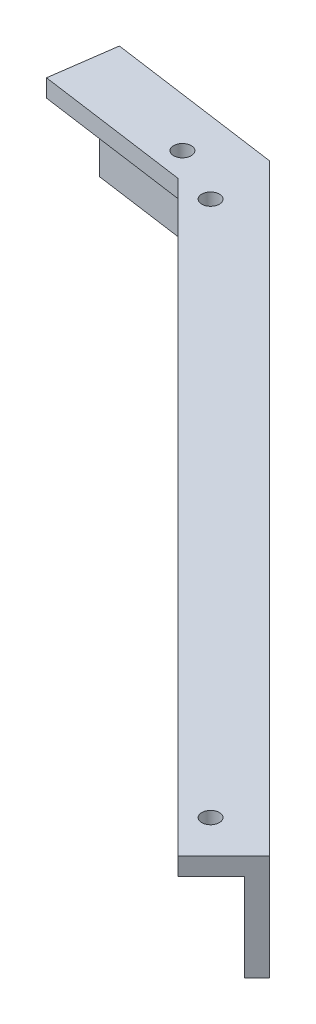
SolidWorks part; units mm, degrees
ref_plane "Alzado" through (0, 0, 0) normal (0, 0, 1) x (1, 0, 0)
ref_plane "Planta" through (0, 0, 0) normal (0, 1, 0) x (1, 0, 0)
ref_plane "Vista lateral" through (0, 0, 0) normal (1, 0, 0) x (0, 0, -1)
sketch "Croquis1" plane through (0, 0, 0) normal (0, 1, 0) x (1, 0, 0)
  line L0 (-35, 0) -> (35, 0) construction
  line L1 (35, 0) -> (65, 0)
  line L2 (65, 0) -> (167.5305, -102.5305)
  line L3 (-35, 0) -> (-65, 0)
  line L4 (-65, 0) -> (-167.5305, -102.5305)
  line L5 (-167.5305, -102.5305) -> (-195, -130) construction
  line L6 (167.5305, -102.5305) -> (195, -130) construction
  line L7 (-167.5305, -102.5305) -> (-161.8736, -108.1873)
  line L8 (167.5305, -102.5305) -> (161.8736, -108.1873)
  line L9 (-161.8736, -108.1873) -> (-61.6863, -8)
  line L10 (-61.6863, -8) -> (-35, -8)
  line L11 (161.8736, -108.1873) -> (61.6863, -8)
  line L12 (61.6863, -8) -> (35, -8)
  line L13 (-35, 0) -> (-35, -8)
  line L14 (35, 0) -> (35, -8)
  line L15 (-65, 0) -> (-62.1716, -2.8284) construction
  line L16 (-62.1716, -2.8284) -> (-67.8284, -8.4853) construction
  line L17 (-67.8284, -8.4853) -> (-159.0452, -99.7021) construction
  line L18 (-159.0452, -99.7021) -> (-164.7021, -105.3589) construction
  line L19 (65, 0) -> (62.1716, -2.8284) construction
  line L20 (62.1716, -2.8284) -> (67.8284, -8.4853) construction
  circle A0 centre (-50, -4) radius 1.5
  circle A1 centre (50, -4) radius 1.5
  circle A2 centre (-67.8284, -8.4853) radius 1.5
  circle A3 centre (-159.0452, -99.7021) radius 1.5
  circle A4 centre (159.0452, -99.7021) radius 1.5
  circle A5 centre (67.8284, -8.4853) radius 1.5
  dimension "D19" = 15
  dimension "D21" = 3
  dimension "D22" = 15
  dimension "D23" = 90
  dimension "D29" = 4
  dimension "D31" = 8
  dimension "D1" = 0
  dimension "D2" = 145
  dimension "D3" = 390
  dimension "D4" = 30
  dimension "D5" = 30
  dimension "D6" = 35
  dimension "D7" = 35
  dimension "D8" = 145
  dimension "D9" = 0
  dimension "D10" = 90
  dimension "D11" = 90
  dimension "D12" = 90
  dimension "D13" = 0
  dimension "D14" = 8
  dimension "D15" = 8
  dimension "D16" = 8
  dimension "D17" = 0
  dimension "D18" = 8
  dimension "D20" = 4
  dimension "D24" = 90
  dimension "D25" = 180
  dimension "D26" = 4
  dimension "D27" = 8
  dimension "D28" = 8
  dimension "D30" = 4
  dimension "D32" = 90
  dimension "D33" = 4
  dimension "D34" = 8
extrude "Saliente-Extruir2" add sketch "Croquis1" along normal blind 3
sketch "Croquis3" plane through (0, 3, 0) normal (0, 1, 0) x (1, 0, 0)
  line L0 (-161.8736, -108.1873) -> (-159.7523, -110.3087)
  line L1 (-159.7523, -110.3087) -> (-60.4437, -11)
  line L2 (-60.4437, -11) -> (-35, -11)
  line L3 (-35, -11) -> (-35, -8)
  line L4 (-167.5305, -102.5305) -> (-161.8736, -108.1873) construction
  line L5 (35, -8) -> (61.6863, -8)
  line L6 (35, -8) -> (35, -11)
  line L7 (35, -11) -> (60.4437, -11)
  line L8 (60.4437, -11) -> (159.7523, -110.3087)
  line L9 (159.7523, -110.3087) -> (161.8736, -108.1873)
  line L10 (61.6863, -8) -> (161.8736, -108.1873) construction
  line L11 (61.6863, -8) -> (161.8736, -108.1873)
  line L12 (-161.8736, -108.1873) -> (-61.6863, -8)
  line L13 (-61.6863, -8) -> (-35, -8)
  dimension "D1" = 3
  dimension "D2" = 180
  dimension "D3" = 90
  dimension "D4" = 3
  dimension "D5" = 90
  dimension "D6" = 90
  dimension "D7" = 3
  dimension "D8" = 3
extrude "Saliente-Extruir3" add sketch "Croquis3" against normal blind 3
sketch "Croquis4" plane through (0, 3, 0) normal (0, 1, 0) x (1, 0, 0)
  line L0 (-67.8284, -8.4853) -> (-65.6364, -10.6773) construction
  line L1 (-65, 0) -> (-167.5305, -102.5305) construction
  line L2 (-156.8532, -101.8941) -> (-159.0452, -99.7021) construction
  line L3 (65.6364, -10.6773) -> (67.8284, -8.4853) construction
  line L4 (167.5305, -102.5305) -> (65, 0) construction
  line L5 (159.0452, -99.7021) -> (156.8532, -101.8941) construction
  circle A0 centre (-50, -7.1) radius 1.5
  circle A1 centre (-50, -4) radius 1.5 construction
  circle A2 centre (-65.6364, -10.6773) radius 1.5
  circle A3 centre (-156.8532, -101.8941) radius 1.5
  circle A4 centre (50, -7.1) radius 1.5
  circle A5 centre (65.6364, -10.6773) radius 1.5
  circle A6 centre (67.8284, -8.4853) radius 1.5 construction
  circle A7 centre (156.8532, -101.8941) radius 1.5
  circle A8 centre (50, -4) radius 1.5 construction
  dimension "D1" = 3.1
  dimension "D2" = 90
  dimension "D4" = 90
  dimension "D6" = 3.1
  dimension "D7" = 90
  dimension "D8" = 90
  dimension "D3" = 3.1
  dimension "D5" = 3.1
  dimension "D9" = 3.1
  dimension "D10" = 3.1
extrude "Cortar-Extruir2" cut sketch "Croquis4" against normal blind 3
sketch "Croquis5" plane through (0, 3, 0) normal (0, 1, 0) x (1, 0, 0)
  circle A0 centre (-159.0452, -99.7021) radius 1.5
  circle A1 centre (-67.8284, -8.4853) radius 1.5
  circle A2 centre (-50, -4) radius 1.5
  circle A3 centre (50, -4) radius 1.5
  circle A4 centre (67.8284, -8.4853) radius 1.5
  circle A5 centre (159.0452, -99.7021) radius 1.5
extrude "Saliente-Extruir4" add sketch "Croquis5" against normal blind 3
sketch "Croquis6" plane through (0, 0, 0) normal (0, -1, 0) x (-1, 0, 0)
  line L0 (167.5305, -102.5305) -> (65, 0)
  line L1 (65, 0) -> (35, 0)
  line L2 (35, 0) -> (65, 0) construction
  line L3 (35, 0) -> (35, -3)
  line L4 (35, -3) -> (63.7574, -3)
  line L5 (63.7574, -3) -> (165.4092, -104.6518)
  line L6 (167.5305, -102.5305) -> (159.7523, -110.3087) construction
  line L7 (165.4092, -104.6518) -> (167.5305, -102.5305)
  line L8 (35, -11) -> (35, 0) construction
  line L9 (-35, 0) -> (-35, -3)
  line L10 (-35, 0) -> (-35, -11) construction
  line L11 (-35, -3) -> (-63.7574, -3)
  line L12 (-63.7574, -3) -> (-165.4092, -104.6518)
  line L13 (-159.7523, -110.3087) -> (-167.5305, -102.5305) construction
  line L14 (-165.4092, -104.6518) -> (-167.5305, -102.5305)
  line L15 (-167.5305, -102.5305) -> (-65, 0)
  line L16 (-65, 0) -> (-35, 0)
  dimension "D1" = 3
  dimension "D2" = 90
  dimension "D3" = 0
  dimension "D4" = 3
  dimension "D5" = 3
  dimension "D6" = 3
extrude "Saliente-Extruir5" add sketch "Croquis6" along normal blind 15
sketch "Croquis7" plane through (0, 0, 0) normal (0, 0, -1) x (-1, 0, 0)
  line L0 (65, -15) -> (35, -15) construction
  circle A0 centre (50, -7.5) radius 1.5
  circle A1 centre (-50, -7.5) radius 1.5
  dimension "D1" = 7.5
extrude "Cortar-Extruir3" cut sketch "Croquis7" against normal blind 15
sketch "Croquis8" plane through (-32.5, 0, -32.5) normal (-0.7071, 0, -0.7071) x (-0.7071, 0, 0.7071)
  line L0 (190.9619, -15) -> (45.9619, -15) construction
  line L1 (190.9619, 3) -> (190.9619, -15) construction
  line L2 (45.9619, 3) -> (45.9619, -15) construction
  circle A0 centre (182.9619, -7.5) radius 1.5
  circle A1 centre (53.9619, -7.5) radius 1.5
  dimension "D1" = 3
  dimension "D4" = 8
  dimension "D2" = 7.5
  dimension "D3" = 8
  dimension "D5" = 7.5
extrude "Cortar-Extruir4" cut sketch "Croquis8" against normal blind 15
sketch "Croquis9" plane through (32.5, 0, -32.5) normal (0.7071, 0, -0.7071) x (-0.7071, 0, -0.7071)
  line L0 (-45.9619, -15) -> (-190.9619, -15) construction
  line L1 (-190.9619, 3) -> (-190.9619, -15) construction
  line L2 (-45.9619, 3) -> (-45.9619, -15) construction
  circle A0 centre (-182.9619, -7.5) radius 1.5
  circle A1 centre (-53.9619, -7.5) radius 1.5
  dimension "D1" = 7.5
  dimension "D3" = 8
  dimension "D2" = 8
extrude "Cortar-Extruir5" cut sketch "Croquis9" against normal blind 15
sketch "Croquis10" plane through (0, 3, 0) normal (0, 1, 0) x (1, 0, 0)
  line L1 (-35, 0) -> (-242.079, 0)
  line L2 (-35, 0) -> (-35, -142.8654)
  line L3 (-35, -142.8654) -> (-242.079, -142.8654)
  line L4 (-242.079, 0) -> (-242.079, -142.8654)
extrude "Cortar-Extruir6" cut sketch "Croquis10" against normal blind 20
sketch "Croquis11" plane through (0, 3, 0) normal (0, 1, 0) x (1, 0, 0)
  line L0 (65, 0) -> (35.2878, 4.1456)
  line L1 (35.2878, 4.1456) -> (33.7678, -6.7489)
  line L2 (33.7678, -6.7489) -> (59.8287, -10.385)
  line L3 (59.8287, -10.385) -> (60.4437, -11)
  line L4 (60.4437, -11) -> (159.7523, -110.3087) construction
  line L5 (167.5305, -102.5305) -> (65, 0) construction
  line L6 (60.4437, -11) -> (65, 0)
  dimension "D1" = 180
  dimension "D2" = 142.943
  dimension "D3" = 30
  dimension "D4" = 11
extrude "Saliente-Extruir6" add sketch "Croquis11" along normal blind 3
sketch "Croquis12" plane through (0, 6, 0) normal (0, 1, 0) x (1, 0, 0)
  line L0 (35, -6.9208) -> (35, -11)
  line L1 (35, -11) -> (60.4437, -11)
  line L2 (60.4437, -11) -> (59.8287, -10.385)
  line L3 (59.8287, -10.385) -> (35, -6.9208)
extrude "Cortar-Extruir9" cut sketch "Croquis12" against normal blind 6
sketch "Croquis13" plane through (0, 6, 0) normal (0, 1, 0) x (1, 0, 0)
  line L0 (35.2878, 4.1456) -> (33.7678, -6.7489)
  line L1 (33.7678, -6.7489) -> (59.8287, -10.385)
  line L2 (59.8287, -10.385) -> (60.4437, -11)
  line L3 (60.4437, -11) -> (65, 0)
  line L4 (65, 0) -> (35.2878, 4.1456)
extrude "Saliente-Extruir8" add sketch "Croquis13" against normal blind 6
sketch "Croquis14" plane through (0, 6, 0) normal (0, 1, 0) x (1, 0, 0)
  line L1 (32.1986, 6.7988) -> (67.5209, 6.7988)
  line L2 (32.1986, 6.7988) -> (32.1986, -22.5472)
  line L3 (32.1986, -22.5472) -> (67.5209, -22.5472)
  line L4 (67.5209, 6.7988) -> (67.5209, -22.5472)
extrude "Cortar-Extruir10" cut sketch "Croquis14" against normal blind 3
sketch "Croquis15" plane through (1.2412, 0, -8.896) normal (0.1382, 0, -0.9904) x (-0.9904, 0, -0.1382)
  line L1 (-64.3764, 0) -> (-28.3331, 0)
  line L2 (-64.3764, 0) -> (-64.3764, -18.3191)
  line L3 (-64.3764, -18.3191) -> (-28.3331, -18.3191)
  line L4 (-28.3331, 0) -> (-28.3331, -18.3191)
extrude "Cortar-Extruir12" cut sketch "Croquis15" against normal blind 10
sketch "Croquis16" plane through (0, 0, 0) normal (0, -1, 0) x (-1, 0, 0)
  line L0 (-65, 0) -> (-35.2878, 4.1456)
  line L1 (-35.2878, 4.1456) -> (-34.8733, 1.1744)
  line L2 (-35.2878, 4.1456) -> (-33.7678, -6.7489) construction
  line L3 (-34.8733, 1.1744) -> (-63.5896, -2.8323)
  line L4 (-63.5896, -2.8323) -> (-64.4805, -3.7232)
  line L5 (-165.4092, -104.6518) -> (-64.4805, -3.7232) construction
  line L6 (-35.2878, 4.1456) -> (-65, 0)
  line L7 (-64.4805, -3.7232) -> (-66.2866, -3.2822)
  line L8 (-66.2866, -3.2822) -> (-65, 0)
  line M3 (-65, 0) -> (-64.4805, -3.7232)
  line M8 (-33.7678, -6.7489) -> (-35.2878, 4.1456)
  line M9 (-35.2878, 4.1456) -> (-65, 0)
  dimension "D1" = 180
  dimension "D2" = 3
extrude "Saliente-Extruir9" add sketch "Croquis16" along normal blind 15 contours L4 L3 M8 M9 M3 | L8 L7 M3
sketch "Croquis17" plane through (0, -15, 0) normal (0, -1, 0) x (-1, 0, 0)
  line L0 (-35.2878, 4.1456) -> (-65, 0) construction
  line L1 (-56.0956, -5.9264) -> (-57.0768, 1.1055) construction
  line L2 (-57.0768, 1.1055) -> (-65, 0) construction
  circle A0 centre (-56.0956, -5.9264) radius 1.5
  dimension "D1" = 7.1
  dimension "D2" = 8
extrude "Cortar-Extruir14" cut sketch "Croquis17" against normal blind 30
sketch "Croquis18" plane through (1.2412, 0, -8.896) normal (0.1382, 0, -0.9904) x (-0.9904, 0, -0.1382)
  line L0 (-64.3764, 3) -> (-34.3764, 3) construction
  line L1 (-56.3764, -4.1) -> (-56.3764, 3) construction
  line L2 (-56.3764, 3) -> (-64.3764, 3) construction
  circle A0 centre (-56.3764, -4.1) radius 1.5
  dimension "D1" = 7.1
  dimension "D2" = 8
extrude "Cortar-Extruir15" cut sketch "Croquis18" against normal blind 30
